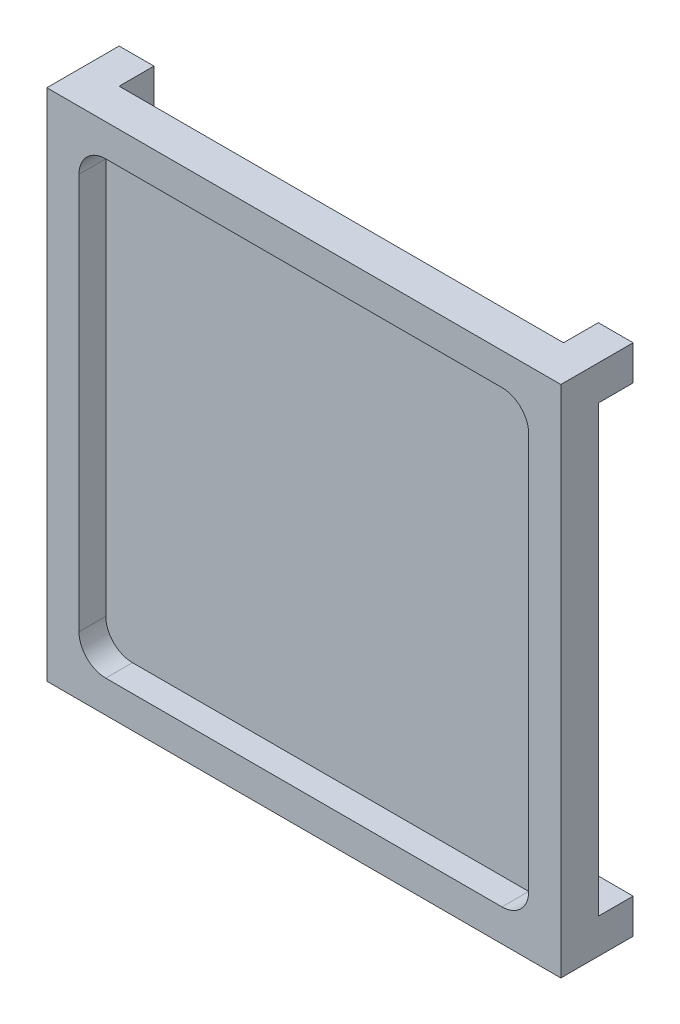
SolidWorks part; units mm, degrees
material "7075-T6 (SN)"
ref_plane "Front Plane" through (0, 0, 0) normal (0, 0, 1) x (1, 0, 0)
ref_plane "Top Plane" through (0, 0, 0) normal (0, 1, 0) x (1, 0, 0)
ref_plane "Right Plane" through (0, 0, 0) normal (1, 0, 0) x (0, 0, -1)
sketch "Sketch1" plane through (0, 0, 0) normal (0, 0, 1) x (1, 0, 0)
  line L1 (48, -48) -> (-48, -48)
  line L2 (48, -48) -> (48, 48)
  line L3 (48, 48) -> (-48, 48)
  line L4 (-48, -48) -> (-48, 48)
  line L5 (48, -48) -> (-48, 48) construction
  line L6 (48, 48) -> (-48, -48) construction
  point P0 (0, 0)
  dimension "D1" = 96
  dimension "D2" = 96
extrude "Boss-Extrude1" add sketch "Sketch1" along normal blind 2
sketch "Sketch2" plane through (0, 0, 2) normal (0, 0, 1) x (1, 0, 0)
  line L0 (48, 48) -> (-48, 48) construction
  line L1 (37, -42) -> (-37, -42)
  line L2 (42, -37) -> (42, 37)
  line L3 (37, 42) -> (-37, 42)
  line L4 (-42, -37) -> (-42, 37)
  line L5 (42, -42) -> (-42, 42) construction
  line L6 (42, 42) -> (-42, -42) construction
  line L7 (48, -48) -> (48, 48) construction
  line L12 (-48, 48) -> (-48, -48)
  line L13 (-48, -48) -> (48, -48)
  line L14 (48, -48) -> (48, 48)
  line L15 (48, 48) -> (-48, 48)
  line L16 (-48, 48) -> (-48, -48)
  line L17 (-48, -48) -> (48, -48)
  line L18 (48, -48) -> (48, 48)
  line L19 (48, 48) -> (-48, 48)
  arc A0 (-37, -42) -> (-42, -37) centre (-37, -37) cw
  arc A1 (37, -42) -> (42, -37) centre (37, -37) ccw
  arc A2 (42, 37) -> (37, 42) centre (37, 37) ccw
  arc A3 (-37, 42) -> (-42, 37) centre (-37, 37) ccw
  point P0 (0, 0)
  dimension "D4" = 5
  dimension "D1" = 6
  dimension "D2" = 6
  dimension "D3" = 0
extrude "Boss-Extrude2" add sketch "Sketch2" along normal blind 5
sketch "Sketch4" plane through (0, 0, 7) normal (0, 0, 1) x (1, 0, 0)
  line L0 (-41.5, 41.5) -> (41.5, -41.5) construction
  line L1 (-41.5, 41.5) -> (41.5, 41.5)
  line L2 (-41.5, 41.5) -> (-41.5, -41.5)
  line L3 (-41.5, -41.5) -> (41.5, -41.5)
  line L4 (41.5, 41.5) -> (41.5, -41.5)
  point P4 (0, 0)
  dimension "D1" = 83
  dimension "D2" = 83
sketch "Sketch3" plane through (0, 0, 0) normal (0, 0, -1) x (-1, 0, 0)
  line L1 (-48, 48) -> (-41.5, 48)
  line L2 (-48, 48) -> (-48, 41.5)
  line L3 (-48, 41.5) -> (-41.5, 41.5)
  line L4 (-41.5, 48) -> (-41.5, 41.5)
  line L5 (48, 48) -> (41.5, 48)
  line L6 (48, 48) -> (48, 41.5)
  line L7 (48, 41.5) -> (41.5, 41.5)
  line L8 (41.5, 48) -> (41.5, 41.5)
  line L9 (-48, -48) -> (-41.5, -48)
  line L10 (-48, -48) -> (-48, -41.5)
  line L11 (-48, -41.5) -> (-41.5, -41.5)
  line L12 (-41.5, -48) -> (-41.5, -41.5)
  line L13 (48, -48) -> (41.5, -48)
  line L14 (48, -48) -> (48, -41.5)
  line L15 (48, -41.5) -> (41.5, -41.5)
  line L16 (41.5, -48) -> (41.5, -41.5)
  dimension "D1" = 6.5
  dimension "D2" = 6.5
  dimension "D3" = 6.5
  dimension "D4" = 6.5
extrude "Boss-Extrude3" add sketch "Sketch3" along normal blind 6.5
equation "\"D2@Sketch1\"=\"D1@Sketch1\""
equation "\"thickness\" = 2"
equation "\"D1@Boss-Extrude1\"=\"thickness\""
equation "\"D2@Sketch2\"=\"D1@Sketch2\""
equation "\"D2@Sketch3\"=\"D1@Sketch3\""
equation "\"D3@Sketch3\"=\"D1@Sketch3\""
equation "\"D4@Sketch3\"=\"D1@Sketch3\""
equation "\"D2@Sketch4\"=\"D1@Sketch4\""
